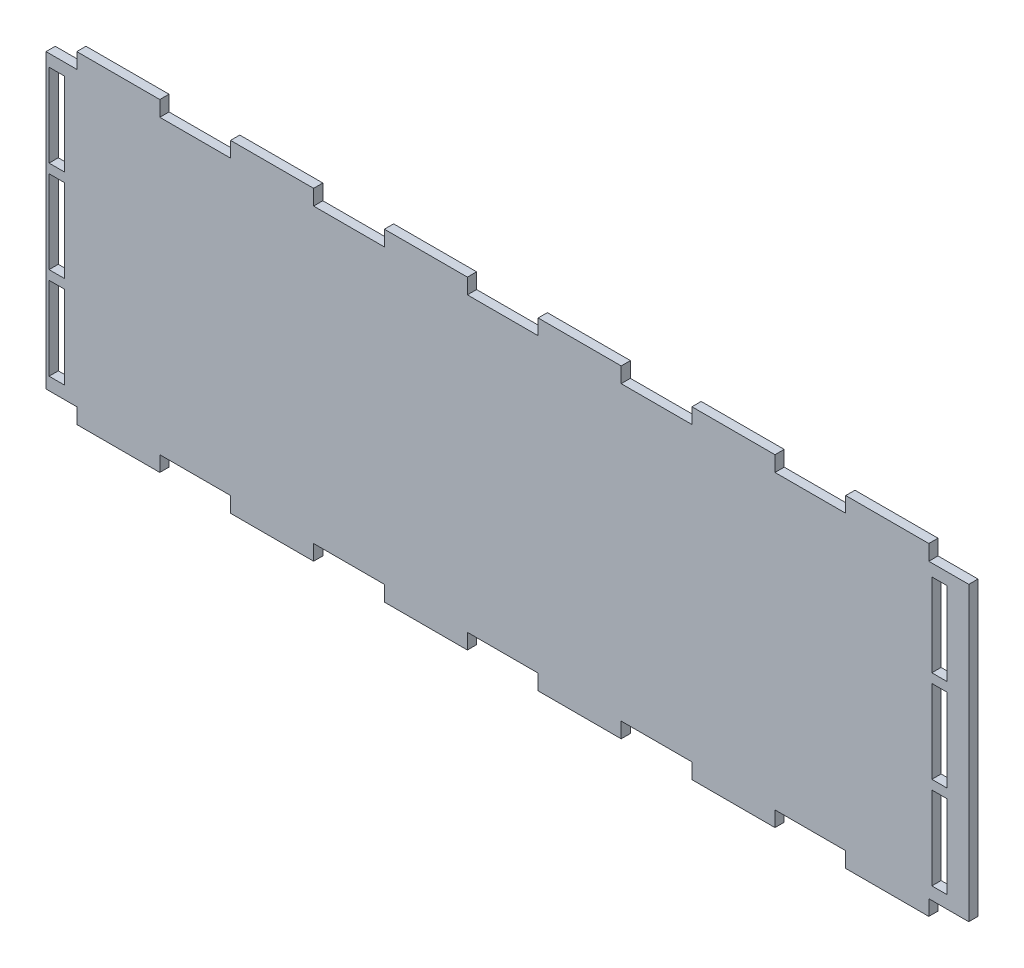
SolidWorks part; units mm, degrees
ref_plane "Plan de face" through (0, 0, 0) normal (0, 0, 1) x (1, 0, 0)
ref_plane "Plan de dessus" through (0, 0, 0) normal (0, 1, 0) x (1, 0, 0)
ref_plane "Plan de droite" through (0, 0, 0) normal (1, 0, 0) x (0, 0, -1)
sketch "Sketch1" plane through (0, 0, 0) normal (0, 0, 1) x (1, 0, 0)
  line L0 (-90, 47.5) -> (-90, 52.5)
  line L1 (150, -47.5) -> (-150, -47.5)
  line L2 (150, -47.5) -> (150, 47.5)
  line L3 (150, 47.5) -> (-150, 47.5)
  line L4 (-150, -47.5) -> (-150, 47.5)
  line L5 (150, -47.5) -> (-150, 47.5) construction
  line L6 (150, 47.5) -> (-150, -47.5) construction
  line L7 (-140, 47.5) -> (-113, 47.5)
  line L8 (-140, 47.5) -> (-140, 52.5)
  line L9 (-140, 52.5) -> (-113, 52.5)
  line L10 (-113, 47.5) -> (-113, 52.5)
  line L11 (-90, 47.5) -> (-63, 47.5)
  line L12 (-63, 47.5) -> (-63, 52.5)
  line L13 (-90, 52.5) -> (-63, 52.5)
  line L14 (-40, 47.5) -> (-40, 52.5)
  line L15 (-40, 47.5) -> (-13, 47.5)
  line L16 (-13, 47.5) -> (-13, 52.5)
  line L17 (-40, 52.5) -> (-13, 52.5)
  line L18 (10, 47.5) -> (10, 52.5)
  line L19 (10, 47.5) -> (37, 47.5)
  line L20 (37, 47.5) -> (37, 52.5)
  line L21 (10, 52.5) -> (37, 52.5)
  line L22 (60, 47.5) -> (60, 52.5)
  line L23 (60, 47.5) -> (87, 47.5)
  line L24 (87, 47.5) -> (87, 52.5)
  line L25 (60, 52.5) -> (87, 52.5)
  line L26 (110, 47.5) -> (110, 52.5)
  line L27 (110, 47.5) -> (137, 47.5)
  line L28 (137, 47.5) -> (137, 52.5)
  line L29 (110, 52.5) -> (137, 52.5)
  line L30 (-149, 13.6026) -> (-149, -13.3974)
  line L35 (-149, 43.6026) -> (-144, 43.6026)
  line L36 (-149, 43.6026) -> (-149, 16.6026)
  line L37 (-149, 16.6026) -> (-144, 16.6026)
  line L38 (-144, 43.6026) -> (-144, 16.6026)
  line L39 (-149, 13.6026) -> (-144, 13.6026)
  line L40 (-144, 13.6026) -> (-144, -13.3974)
  line L41 (-149, -13.3974) -> (-144, -13.3974)
  line L42 (-149, -16.3974) -> (-149, -43.3974)
  line L43 (-149, -16.3974) -> (-144, -16.3974)
  line L44 (-144, -16.3974) -> (-144, -43.3974)
  line L45 (-149, -43.3974) -> (-144, -43.3974)
  line L46 (-90, -47.5) -> (-90, -52.5)
  line L47 (-140, -47.5) -> (-113, -47.5)
  line L48 (-140, -47.5) -> (-140, -52.5)
  line L49 (-140, -52.5) -> (-113, -52.5)
  line L50 (-113, -47.5) -> (-113, -52.5)
  line L51 (-90, -47.5) -> (-63, -47.5)
  line L52 (-63, -47.5) -> (-63, -52.5)
  line L53 (-90, -52.5) -> (-63, -52.5)
  line L54 (-40, -47.5) -> (-40, -52.5)
  line L55 (-40, -47.5) -> (-13, -47.5)
  line L56 (-13, -47.5) -> (-13, -52.5)
  line L57 (-40, -52.5) -> (-13, -52.5)
  line L58 (10, -47.5) -> (10, -52.5)
  line L59 (10, -47.5) -> (37, -47.5)
  line L60 (37, -47.5) -> (37, -52.5)
  line L61 (10, -52.5) -> (37, -52.5)
  line L62 (60, -47.5) -> (60, -52.5)
  line L63 (60, -47.5) -> (87, -47.5)
  line L64 (87, -47.5) -> (87, -52.5)
  line L65 (60, -52.5) -> (87, -52.5)
  line L66 (110, -47.5) -> (110, -52.5)
  line L67 (110, -47.5) -> (137, -47.5)
  line L68 (137, -47.5) -> (137, -52.5)
  line L69 (110, -52.5) -> (137, -52.5)
  point P0 (0, 0)
  dimension "D1" = 300
  dimension "D2" = 95
  dimension "D3" = 10
  dimension "D4" = 5
  dimension "D5" = 27
  dimension "D7" = 27
  dimension "D8" = 5
  dimension "D9" = 4
  dimension "D10" = 3
  dimension "D11" = 27
  dimension "D12" = 5
  dimension "D13" = 10
  dimension "D6" = 6
  dimension "D14" = 6
extrude "Boss-Extrude1" add sketch "Sketch1" along normal blind 3 contours L4 L1 L2 L3 | L3 L10 L9 L8 | L13 L0 L3 L12 | L17 L14 L3 L16 | L21 L18 L3 L20 | L25 L24 L23 L22 | L29 L28 L27 L26
sketch "Sketch2" plane through (0, 0, 3) normal (0, 0, 1) x (1, 0, 0)
  line L0 (137, 47.5) -> (137, 52.5) construction
  line L1 (138, 43.6) -> (143, 43.6)
  line L2 (138, 43.6) -> (138, 16.6)
  line L3 (138, 16.6) -> (143, 16.6)
  line L4 (143, 43.6) -> (143, 16.6)
  line L5 (150, 47.5) -> (137, 47.5) construction
  line L6 (138, 13.6) -> (138, -13.4)
  line L7 (138, 13.6) -> (143, 13.6)
  line L8 (143, 13.6) -> (143, -13.4)
  line L9 (138, -13.4) -> (143, -13.4)
  line L10 (138, -16.4) -> (138, -43.4)
  line L11 (138, -16.4) -> (143, -16.4)
  line L12 (143, -16.4) -> (143, -43.4)
  line L13 (138, -43.4) -> (143, -43.4)
  dimension "D1" = 1
  dimension "D2" = 3.9
  dimension "D3" = 27
  dimension "D4" = 5
  dimension "D5" = 3
extrude "Cut-Extrude1" cut sketch "Sketch2" against normal blind 10
sketch "Sketch3" plane through (0, 0, 3) normal (0, 0, 1) x (1, 0, 0)
  line L0 (150, -47.5) -> (-150, -47.5) construction
  line L1 (-140, -47.5) -> (-113, -47.5)
  line L2 (-140, -47.5) -> (-140, -52.5)
  line L3 (-140, -52.5) -> (-113, -52.5)
  line L4 (-113, -47.5) -> (-113, -52.5)
  line L5 (-150, -47.5) -> (-150, 47.5) construction
  line L6 (-90, -47.5) -> (-90, -52.5)
  line L7 (-90, -47.5) -> (-63, -47.5)
  line L8 (-63, -47.5) -> (-63, -52.5)
  line L9 (-90, -52.5) -> (-63, -52.5)
  line L10 (-40, -47.5) -> (-40, -52.5)
  line L11 (-40, -47.5) -> (-13, -47.5)
  line L12 (-13, -47.5) -> (-13, -52.5)
  line L13 (-40, -52.5) -> (-13, -52.5)
  line L14 (10, -47.5) -> (10, -52.5)
  line L15 (10, -47.5) -> (37, -47.5)
  line L16 (37, -47.5) -> (37, -52.5)
  line L17 (10, -52.5) -> (37, -52.5)
  line L18 (60, -47.5) -> (60, -52.5)
  line L19 (60, -47.5) -> (87, -47.5)
  line L20 (87, -47.5) -> (87, -52.5)
  line L21 (60, -52.5) -> (87, -52.5)
  line L22 (110, -47.5) -> (110, -52.5)
  line L23 (110, -47.5) -> (137, -47.5)
  line L24 (137, -47.5) -> (137, -52.5)
  line L25 (110, -52.5) -> (137, -52.5)
  dimension "D1" = 10
  dimension "D2" = 27
  dimension "D3" = 5
  dimension "D4" = 6
extrude "Boss-Extrude3" add sketch "Sketch3" against normal blind 3
